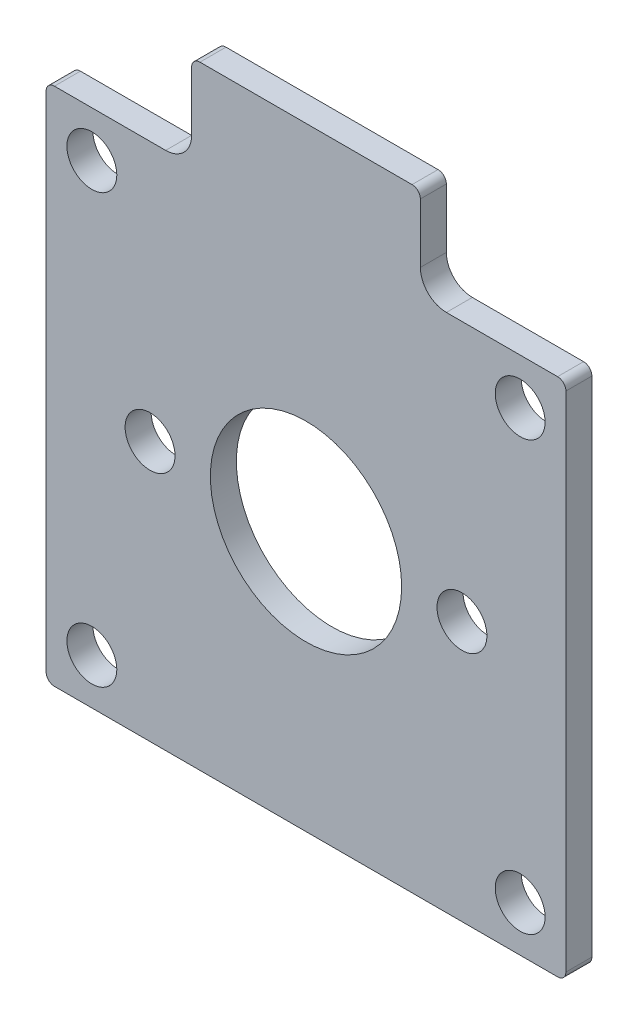
SolidWorks part; units mm, degrees
material "Delrin 2700 NC010, Low Viscosity Acetal Copolymer (SS)"
ref_plane "Front Plane" through (0, 0, 0) normal (0, 0, 1) x (1, 0, 0)
ref_plane "Top Plane" through (0, 0, 0) normal (0, 1, 0) x (1, 0, 0)
ref_plane "Right Plane" through (0, 0, 0) normal (1, 0, 0) x (0, 0, -1)
sketch "Sketch1" plane through (0, 0, 0) normal (0, 0, 1) x (1, 0, 0)
  line L1 (15.367, 15.875) -> (-15.367, 15.875)
  line L2 (15.875, 15.367) -> (15.875, -15.367)
  line L3 (15.367, -15.875) -> (-15.367, -15.875)
  line L4 (-15.875, 15.367) -> (-15.875, -15.367)
  line L5 (15.875, 15.875) -> (-15.875, -15.875) construction
  line L6 (15.875, -15.875) -> (-15.875, 15.875) construction
  arc A0 (-15.367, 15.875) -> (-15.875, 15.367) centre (-15.367, 15.367) ccw
  arc A1 (15.875, -15.367) -> (15.367, -15.875) centre (15.367, -15.367) cw
  arc A2 (15.367, 15.875) -> (15.875, 15.367) centre (15.367, 15.367) cw
  arc A3 (-15.367, -15.875) -> (-15.875, -15.367) centre (-15.367, -15.367) cw
  point P0 (0, 0)
  dimension "D2" = 0.508
  dimension "D1" = 31.75
extrude "Boss-Extrude1" add sketch "Sketch1" along normal blind 1.5875
sketch "Sketch2" plane through (0, 0, 1.5875) normal (0, 0, 1) x (1, 0, 0)
  circle A0 centre (0, 0) radius 5.842
  dimension "D1" = 11.684
extrude "Cut-Extrude1" cut sketch "Sketch2" against normal through all
hole_wizard "#4 Clearance Hole1" positions "Sketch3" profile "Sketch4" hole size "#4" standard "ANSI Inch" end condition through all
sketch "Sketch3" plane through (0, 0, 1.5875) normal (0, 0, 1) x (1, 0, 0)
  line L0 (0, 0) -> (0, 50000) construction
  line L1 (0, 0) -> (50000, 0) construction
  point P0 (-13.081, 13.081)
  point P10 (13.081, 13.081)
  point P11 (13.081, -13.081)
  point P12 (-13.081, -13.081)
  point P13 (-9.525, 0)
  point P17 (0, 0)
  point P18 (-6.7623, 5.0928)
  point P19 (0, 0)
  point P20 (-9.0917, 0)
  point P21 (9.525, 0)
  dimension "D1" = 26.162
  dimension "D2" = 26.162
  dimension "D3" = 19.05
sketch "Sketch4" plane through (-13.081, 13.081, 1.5875) normal (1, 0, 0) x (0, -1, 0)
  line L0 (0, 0) -> (0, 1.5875)
  line L1 (0, 1.5875) -> (1.524, 1.5875)
  line L2 (1.524, 1.5875) -> (1.524, 0)
  line L5 (1.524, 0) -> (0, 0)
  line L11 (0, -6.35) -> (0, 107.95) construction
  dimension "Thru Hole Dia." = 3.048
  dimension "Thru Hole Depth" = 1.5875
sketch "Sketch5" plane through (0, 0, 1.5875) normal (0, 0, 1) x (1, 0, 0)
  line L0 (15.367, 15.875) -> (-15.367, 15.875) construction
  line L1 (6.985, 21.59) -> (-6.985, 21.59)
  line L2 (6.985, 21.59) -> (6.985, 10.16)
  line L3 (6.985, 10.16) -> (-6.985, 10.16)
  line L4 (-6.985, 21.59) -> (-6.985, 10.16)
  line L5 (6.985, 21.59) -> (-6.985, 10.16) construction
  line L6 (6.985, 10.16) -> (-6.985, 21.59) construction
  point P0 (0, 15.875)
  dimension "D1" = 13.97
  dimension "D2" = 5.715
extrude "Boss-Extrude2" add sketch "Sketch5" against normal through all
fillet "Fillet1" radius 1.5875 2 edges at (6.985, 15.875, 0.7937) (-6.985, 15.875, 0.7937)
fillet "Fillet2" radius 0.508 2 edges at (6.985, 21.59, 0.7937) (-6.985, 21.59, 0.7937)
